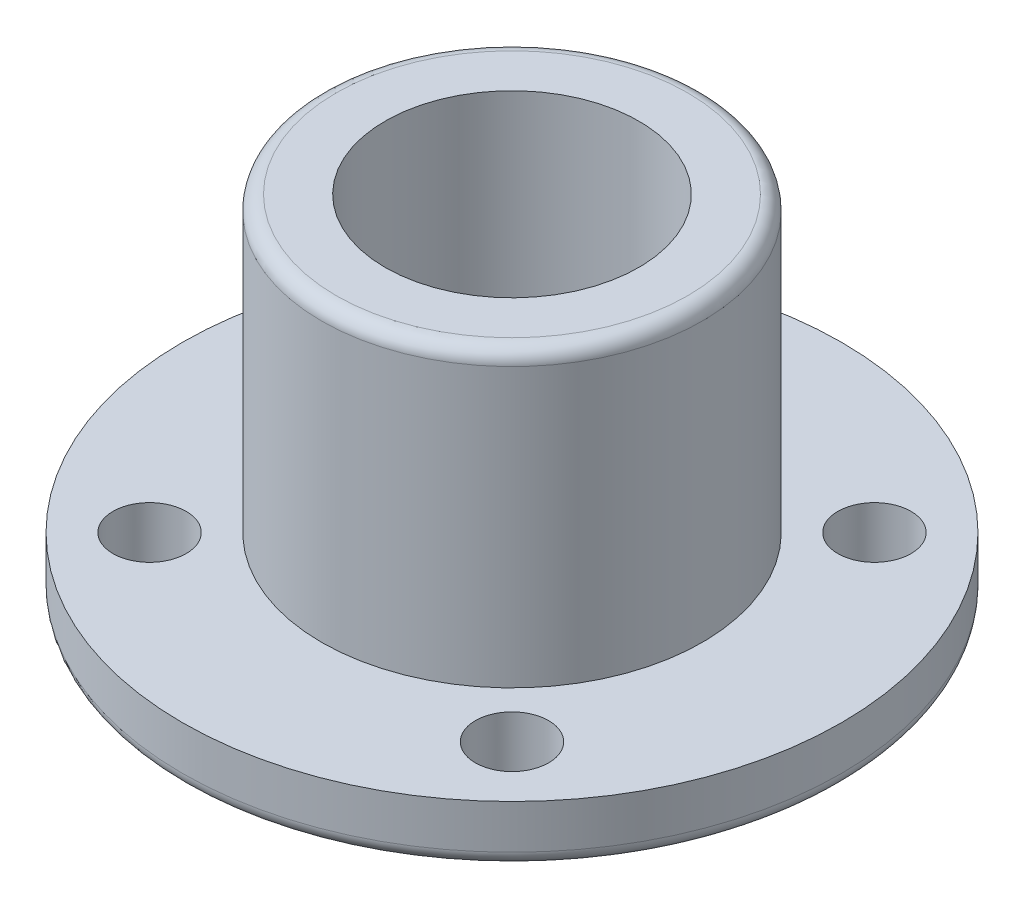
SolidWorks part; units mm, degrees
material "ABS PC"
ref_plane "Front Plane" through (0, 0, 0) normal (0, 0, 1) x (1, 0, 0)
ref_plane "Top Plane" through (0, 0, 0) normal (0, 1, 0) x (1, 0, 0)
ref_plane "Right Plane" through (0, 0, 0) normal (1, 0, 0) x (0, 0, -1)
sketch "Sketch1" plane through (0, 0, 0) normal (0, 1, 0) x (1, 0, 0)
  circle A0 centre (0, 0) radius 28.575
  dimension "D1" = 57.15
extrude "Boss-Extrude1" add sketch "Sketch1" along normal blind 5.08
sketch "Sketch2" plane through (0, 5.08, 0) normal (0, 1, 0) x (1, 0, 0)
  circle A0 centre (0, 0) radius 16.51
  dimension "D1" = 33.02
extrude "Boss-Extrude2" add sketch "Sketch2" along normal blind 25.4
hole_wizard "1/4 (0.25) Diameter Hole1" positions "Sketch3" profile "Sketch4" hole size "1/4" standard "ANSI Inch"
sketch "Sketch3" plane through (0, 0, 0) normal (0, -1, 0) x (-1, 0, 0)
  line L0 (0, 0) -> (0, 22.225) construction
  circle A0 centre (0, 0) radius 22.225 construction
  point P0 (15.7154, 15.7154)
  point P2 (-15.7154, 15.7154)
  point P4 (-15.7154, -15.7154)
  point P6 (15.7154, -15.7154)
  dimension "D1" = 45
  dimension "D2" = 90
  dimension "D3" = 90
  dimension "D4" = 90
sketch "Sketch4" plane through (-15.7154, 0, -15.7154) normal (1, 0, 0) x (0, 0, -1)
  line L0 (0, 0) -> (0, 10.7977)
  line L1 (0, 10.7977) -> (3.175, 8.89)
  line L2 (3.175, 8.89) -> (3.175, 0)
  line L5 (3.175, 0) -> (0, 0)
  line L10 (0, 10.7977) -> (-3.175, 8.89) construction
  line L11 (0, -6.35) -> (0, 107.95) construction
  dimension "Hole Dia." = 6.35
  dimension "Hole Depth" = 8.89
  dimension "Drill Angle" = 118
sketch "Sketch5" plane through (0, 30.48, 0) normal (0, 1, 0) x (1, 0, 0)
  circle A0 centre (0, 0) radius 11
  dimension "D1" = 22
extrude "Cut-Extrude1" cut sketch "Sketch5" against normal through all and the other way through all
fillet "Fillet1" radius 1.27 2 edges at (0, 30.48, 16.51) (0, 0, 28.575)
